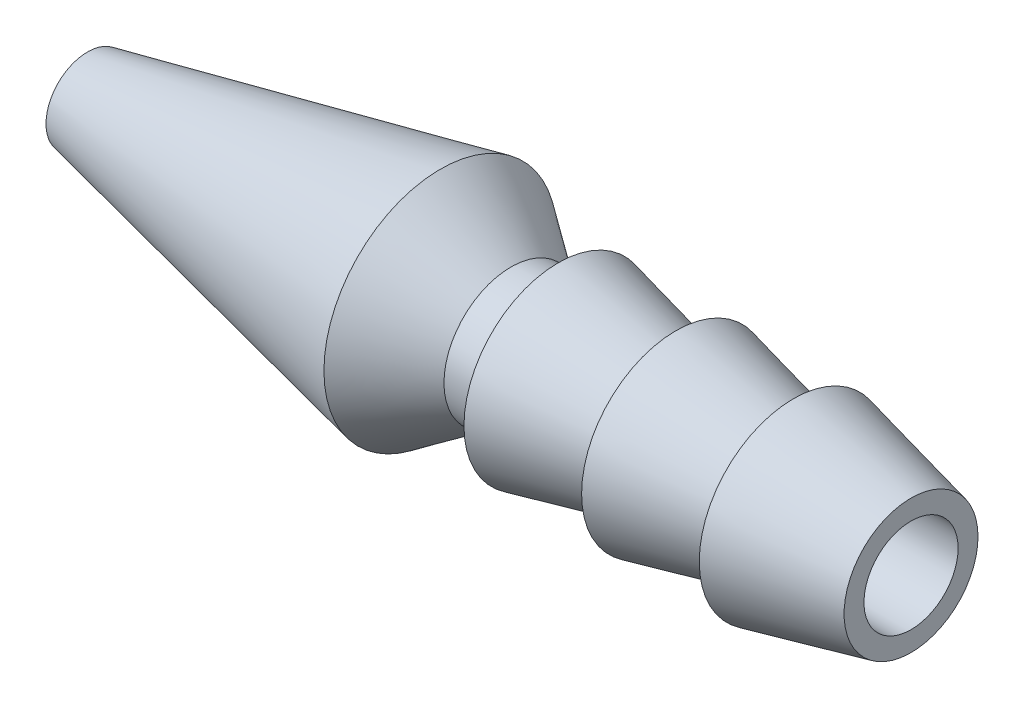
SolidWorks part; units mm, degrees
ref_plane "Front Plane" through (0, 0, 0) normal (0, 0, 1) x (1, 0, 0)
ref_plane "Top Plane" through (0, 0, 0) normal (0, 1, 0) x (1, 0, 0)
ref_plane "Right Plane" through (0, 0, 0) normal (1, 0, 0) x (0, 0, -1)
sketch "Sketch1" plane through (0, 0, 0) normal (1, 0, 0) x (0, 0, -1)
  circle A0 centre (0, 0) radius 4
extrude "Boss-Extrude1" add sketch "Sketch1" along normal blind 5 draft 13
sketch "Sketch2" plane through (5, 0, 0) normal (1, 0, 0) x (0, 0, -1)
  circle A0 centre (0, 0) radius 4
extrude "Boss-Extrude2" add sketch "Sketch2" along normal blind 5 draft 13
sketch "Sketch3" plane through (10, 0, 0) normal (1, 0, 0) x (0, 0, -1)
  circle A0 centre (0, 0) radius 4
extrude "Boss-Extrude3" add sketch "Sketch3" along normal blind 5 draft 13
sketch "Sketch4" plane through (0, 0, 0) normal (-1, 0, 0) x (0, 0, 1)
  circle A0 centre (0, 0) radius 2.85
extrude "Boss-Extrude4" add sketch "Sketch4" along normal blind 2
sketch "Sketch5" plane through (-2, 0, 0) normal (-1, 0, 0) x (0, 0, 1)
  circle A0 centre (0, 0) radius 2.85
extrude "Boss-Extrude5" add sketch "Sketch5" along normal blind 3 draft 35 draft outward yes
sketch "Sketch6" plane through (-5, 0, 0) normal (-1, 0, 0) x (0, 0, 1)
  circle A0 centre (0, 0) radius 4.9506
extrude "Boss-Extrude6" add sketch "Sketch6" along normal blind 15 draft 12
sketch "Sketch9" plane through (15, 0, 0) normal (1, 0, 0) x (0, 0, -1)
  circle A0 centre (0, 0) radius 2
extrude "Cut-Extrude1" cut sketch "Sketch9" against normal blind 20
sketch "Sketch12" plane through (-20, 0, 0) normal (-1, 0, 0) x (0, 0, 1)
  line L1 (-1.25, 0.4) -> (1.25, 0.4)
  line L2 (-1.25, 0.4) -> (-1.25, -0.4)
  line L3 (-1.25, -0.4) -> (1.25, -0.4)
  line L4 (1.25, 0.4) -> (1.25, -0.4)
  line L5 (-1.25, 0.4) -> (1.25, -0.4) construction
  line L6 (-1.25, -0.4) -> (1.25, 0.4) construction
  point P0 (0, 0)
  dimension "D1" = 2.5
  dimension "D2" = 0.8
extrude "Cut-Extrude6" cut sketch "Sketch12" against normal blind 10 draft 2.8
sketch "Sketch13" plane through (-5, 0, 0) normal (1, 0, 0) x (0, 0, -1)
  circle A0 centre (0, 0) radius 2
extrude "Cut-Extrude9" cut sketch "Sketch13" against normal blind 15 draft 6.2
